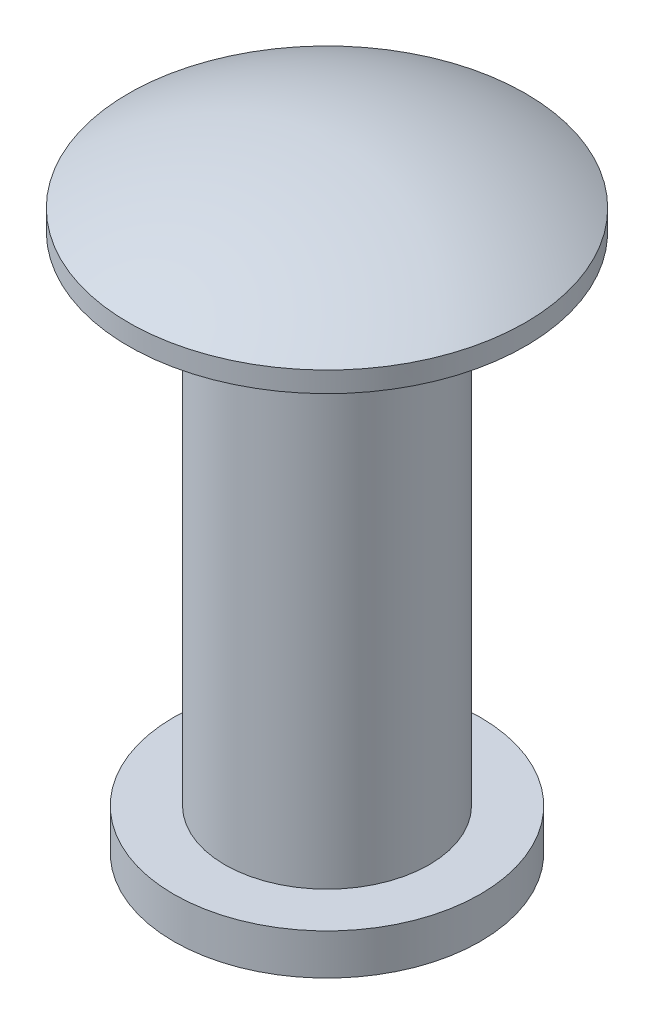
SolidWorks part; units mm, degrees
ref_plane "Спереди" through (0, 0, 0) normal (0, 0, 1) x (1, 0, 0)
ref_plane "Сверху" through (0, 0, 0) normal (0, 1, 0) x (1, 0, 0)
ref_plane "Справа" through (0, 0, 0) normal (1, 0, 0) x (0, 0, -1)
sketch "Эскиз1" plane through (0, 0, 0) normal (0, 0, 1) x (1, 0, 0)
  line L2 (5, 0) -> (7.5, 0)
  line L3 (7.5, 0) -> (7.5, -2)
  line L4 (2.5, -2) -> (2.5, 26.5)
  line L5 (2.5, 26.5) -> (0, 26.5)
  line L6 (0, 26.5) -> (0, 28)
  line L7 (2.5, -2) -> (7.5, -2)
  line L8 (0, -22.0432) -> (0, 37.9568) construction
  line L9 (2.5, 26) -> (3.75, 26)
  line L10 (3.75, 26) -> (3.75, -2)
  line L11 (5, 0) -> (5, 27.3303)
  line L12 (5, 25.3303) -> (9.7119, 25.3303)
  line L13 (-15, -2.6619) -> (15, -2.6619) construction
  line L14 (9.7119, 25.3303) -> (5, 25.3303)
  line L15 (9.7119, 25.3303) -> (9.7119, 24.3303)
  line L16 (9.7119, 24.3303) -> (5, 24.3303)
  line L17 (5, 25.3303) -> (5, 24.3303)
  circle A1 centre (0, 9) radius 19
  dimension "D9" = 5
  dimension "D6" = 38
  dimension "D10" = 2
  dimension "D1" = 1.5
  dimension "D2" = 2.5
  dimension "D3" = 3.75
  dimension "D4" = 2
  dimension "D5" = 2.5
  dimension "D7" = 28.5
  dimension "D8" = 28
  dimension "D11" = 1
  dimension "D12" = 30
  dimension "D13" = 0.6619
  dimension "D14" = 5
  dimension "D15" = 7.5
revolve "Повернуть1" add sketch "Эскиз1" angle 360 about L8
ref_plane "Плоскость1" through (0, -2.6619, 0) normal (0, 1, 0) x (1, 0, 0)
sketch "Эскиз2" plane through (0, -2.6619, 0) normal (0, 1, 0) x (1, 0, 0)
  circle A0 centre (0, 0) radius 15
  dimension "D1" = 30
